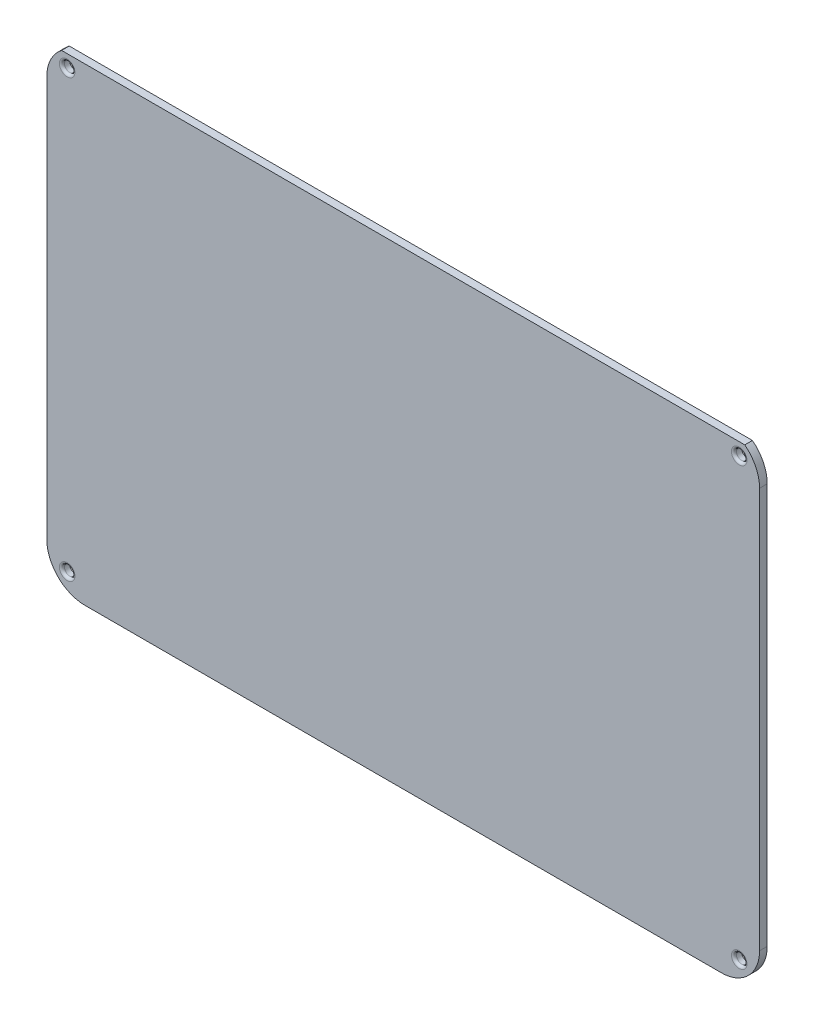
SolidWorks part; units mm, degrees
material "PET"
ref_plane "Front Plane" through (0, 0, 0) normal (0, 0, 1) x (1, 0, 0)
ref_plane "Top Plane" through (0, 0, 0) normal (0, 1, 0) x (1, 0, 0)
ref_plane "Right Plane" through (0, 0, 0) normal (1, 0, 0) x (0, 0, -1)
sketch "Sketch2" plane through (0, 0, 0) normal (0, 0, 1) x (-1, 0, 0)
  line L8 (-134.1895, -184.2055) -> (134.1895, -184.2055)
  line L9 (-127, -10) -> (-127, -177.3499)
  line L10 (125, -179.3499) -> (-125, -179.3499)
  line L11 (127, -10) -> (127, -177.3499)
  line L12 (125, -8) -> (-125, -8)
  line L13 (-140, -15) -> (-140, -172.3499)
  line L14 (140, -15) -> (140, -172.3499)
  line L15 (125, 0) -> (-125, 0)
  arc A8 (-125, -8) -> (-127, -10) centre (-125, -10) ccw
  arc A9 (-127, -177.3499) -> (-125, -179.3499) centre (-125, -177.3499) ccw
  arc A10 (125, -179.3499) -> (127, -177.3499) centre (125, -177.3499) ccw
  arc A11 (127, -10) -> (125, -8) centre (125, -10) ccw
  arc A12 (-140, -172.3499) -> (-134.1895, -184.2055) centre (-125, -172.3499) ccw
  arc A13 (134.1895, -184.2055) -> (140, -172.3499) centre (125, -172.3499) ccw
  arc A14 (140, -15) -> (125, 0) centre (125, -15) ccw
  arc A15 (-125, 0) -> (-140, -15) centre (-125, -15) ccw
  circle A20 centre (-132, -179.3499) radius 2.05
  circle A21 centre (-132, -8) radius 2.05
  circle A22 centre (132, -8) radius 2.05
  circle A23 centre (132, -179.3499) radius 2.05
  point P25 (0, 0)
extrude "Boss-Extrude1" add sketch "Sketch2" along normal blind 3 contours L15 A15 L13 A12 L8 A13 L14 A14 A23 A22 A21 A20 A11 L11 A10 L10 A9 L9 A8 L12 | L11 A11 L12 A8 L9 A9 L10 A10
sketch "Sketch3" plane through (0, 0, 0) normal (0, 0, -1) x (-1, 0, 0)
  line L0 (-126.6, 177.3499) -> (-126.6, 10)
  line L1 (-125, 8.4) -> (125, 8.4)
  line L2 (126.6, 10) -> (126.6, 177.3499)
  line L3 (125, 178.9499) -> (-125, 178.9499)
  line L4 (-127, 177.3499) -> (-127, 10)
  line L5 (125, 179.3499) -> (-125, 179.3499)
  line L6 (127, 10) -> (127, 177.3499)
  line L7 (-125, 8) -> (125, 8)
  line L8 (-127, 177.3499) -> (-127, 10)
  line L9 (125, 179.3499) -> (-125, 179.3499)
  line L10 (127, 10) -> (127, 177.3499)
  line L11 (-125, 8) -> (125, 8)
  line L12 (-140, 172.3499) -> (-140, 15)
  line L13 (134.1895, 184.2055) -> (-134.1895, 184.2055)
  line L14 (140, 15) -> (140, 172.3499)
  line L15 (-125, 0) -> (125, 0)
  line L16 (-140, 172.3499) -> (-140, 15)
  line L17 (134.1895, 184.2055) -> (-134.1895, 184.2055)
  line L18 (140, 15) -> (140, 172.3499)
  line L19 (-125, 0) -> (125, 0)
  arc A0 (-126.6, 10) -> (-125, 8.4) centre (-125, 10) ccw
  circle A1 centre (132, 179.3499) radius 2.05
  circle A2 centre (132, 179.3499) radius 2.05
  circle A3 centre (132, 8) radius 2.05
  arc A4 (-125, 179.3499) -> (-127, 177.3499) centre (-125, 177.3499) ccw
  arc A5 (127, 177.3499) -> (125, 179.3499) centre (125, 177.3499) ccw
  arc A6 (125, 8) -> (127, 10) centre (125, 10) ccw
  arc A7 (-127, 10) -> (-125, 8) centre (-125, 10) ccw
  arc A8 (-125, 179.3499) -> (-127, 177.3499) centre (-125, 177.3499) ccw
  arc A9 (127, 177.3499) -> (125, 179.3499) centre (125, 177.3499) ccw
  arc A10 (125, 8) -> (127, 10) centre (125, 10) ccw
  arc A11 (-127, 10) -> (-125, 8) centre (-125, 10) ccw
  arc A12 (-134.1895, 184.2055) -> (-140, 172.3499) centre (-125, 172.3499) ccw
  arc A13 (140, 172.3499) -> (134.1895, 184.2055) centre (125, 172.3499) ccw
  arc A14 (125, 0) -> (140, 15) centre (125, 15) ccw
  arc A15 (-140, 15) -> (-125, 0) centre (-125, 15) ccw
  arc A16 (-134.1895, 184.2055) -> (-140, 172.3499) centre (-125, 172.3499) ccw
  arc A17 (140, 172.3499) -> (134.1895, 184.2055) centre (125, 172.3499) ccw
  arc A18 (125, 0) -> (140, 15) centre (125, 15) ccw
  arc A19 (-140, 15) -> (-125, 0) centre (-125, 15) ccw
  circle A20 centre (132, 8) radius 2.05
  circle A21 centre (-132, 8) radius 2.05
  circle A22 centre (-132, 8) radius 2.05
  circle A23 centre (-132, 179.3499) radius 2.05
  circle A24 centre (-132, 179.3499) radius 2.05
  arc A25 (125, 8.4) -> (126.6, 10) centre (125, 10) ccw
  arc A26 (126.6, 177.3499) -> (125, 178.9499) centre (125, 177.3499) ccw
  arc A27 (-125, 178.9499) -> (-126.6, 177.3499) centre (-125, 177.3499) ccw
  dimension "D1" = 0
  dimension "D2" = 0
  dimension "D3" = 0
  dimension "D4" = 0
  dimension "D5" = 0
  dimension "D6" = 0
  dimension "D7" = 0.4
extrude "Boss-Extrude2" add sketch "Sketch3" along normal blind 3 contours L2 A26 L3 A27 L0 A0 L1 A25
fillet "Fillet1" radius 1 4 edges at (-129.95, 8, 3) (-129.95, 179.3499, 3) (134.05, 179.3499, 3) (134.05, 8, 3)
